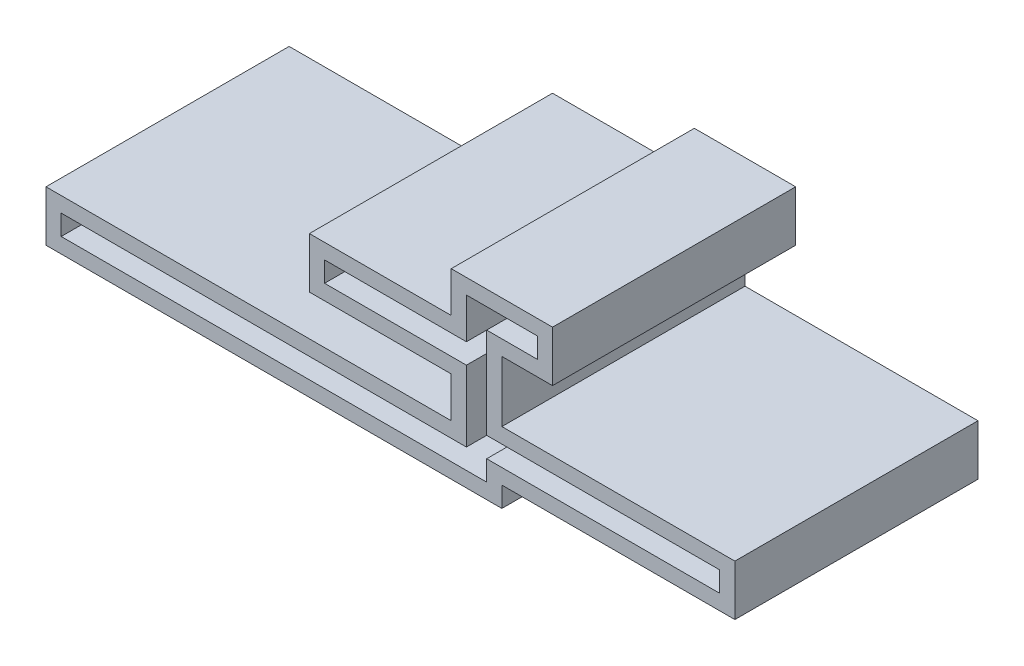
SolidWorks part; units mm, degrees
ref_plane "Front Plane" through (0, 0, 0) normal (0, 0, 1) x (1, 0, 0)
ref_plane "Top Plane" through (0, 0, 0) normal (0, 1, 0) x (1, 0, 0)
ref_plane "Right Plane" through (0, 0, 0) normal (1, 0, 0) x (0, 0, -1)
sketch "Sketch1" plane through (0, 0, 0) normal (0, 0, 1) x (1, 0, 0)
  line L0 (-241.3, 177.8) -> (-63.5, 177.8)
  line L1 (-63.5, 228.6) -> (-63.5, 177.8)
  line L2 (-63.5, 228.6) -> (63.5, 228.6)
  line L3 (63.5, 228.6) -> (63.5, 165.1)
  line L4 (63.5, 165.1) -> (0, 165.1)
  line L5 (0, 165.1) -> (0, 88.9)
  line L6 (0, 88.9) -> (292.1, 88.9)
  line L7 (292.1, 88.9) -> (292.1, 25.4)
  line L8 (292.1, 25.4) -> (0, 25.4)
  line L9 (0, 25.4) -> (0, 0)
  line L10 (0, 0) -> (-571.5, 0)
  line L11 (-571.5, 0) -> (-571.5, 63.5)
  line L12 (-571.5, 63.5) -> (-63.5, 63.5)
  line L13 (-63.5, 63.5) -> (-63.5, 114.3)
  line L14 (-63.5, 114.3) -> (-241.3, 114.3)
  line L15 (-241.3, 114.3) -> (-241.3, 177.8)
  line L16 (0, 25.4) -> (-63.5, 25.4) construction
  dimension "D1" = 63.5
  dimension "D2" = 50.8
  dimension "D3" = 508
  dimension "D4" = 127
  dimension "D5" = 177.8
  dimension "D6" = 292.1
  dimension "D7" = 76.2
  dimension "D8" = 50.8
extrude "Boss-Extrude1" add sketch "Sketch1" along normal blind 304.8
shell "Shell1" thickness 19.05
